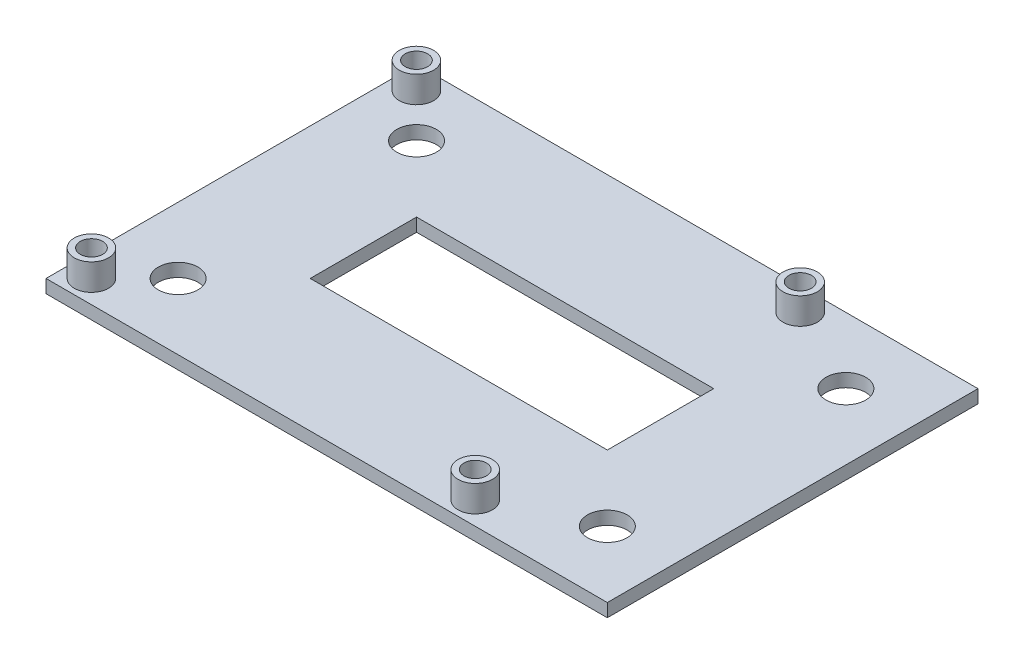
SolidWorks part; units mm, degrees
ref_plane "Front Plane" through (0, 0, 0) normal (0, 0, 1) x (1, 0, 0)
ref_plane "Top Plane" through (0, 0, 0) normal (0, 1, 0) x (1, 0, 0)
ref_plane "Right Plane" through (0, 0, 0) normal (1, 0, 0) x (0, 0, -1)
sketch "Base plate" plane through (0, 0, 0) normal (0, 1, 0) x (1, 0, 0)
  line L0 (-13.8721, -27.7771) -> (51.1097, -27.7771) construction
  line L1 (-13.8721, 23.7265) -> (71.1279, 23.7265)
  line L2 (-13.8721, 23.7265) -> (-13.8721, -32.3735)
  line L3 (71.1097, -32.3735) -> (71.1279, 23.7265)
  line L4 (47.6597, -28.9235) -> (-10.4403, -28.9235) construction
  line L7 (-13.8721, -32.3735) -> (71.1097, -32.3735) construction
  line L10 (71.1097, -32.3735) -> (-13.8721, -32.3735)
  line L24 (-10.4403, 20.2765) -> (-13.8721, 20.2765) construction
  line L25 (-10.4403, 23.7265) -> (-10.4403, 20.2765) construction
  line L26 (47.6597, 23.7265) -> (47.6597, 20.2765) construction
  line L27 (51.1097, 20.2765) -> (47.6597, 20.2765) construction
  line L28 (51.1097, -28.9235) -> (47.6597, -28.9235) construction
  line L29 (47.6597, -28.9235) -> (47.6597, -32.3735) construction
  point P12 (-13.8721, -32.3735)
  point P15 (-13.8721, 23.7265)
  point P34 (71.1279, 23.7265)
sketch "Base plate inner limits" plane through (0, 0, 0) normal (0, 1, 0) x (1, 0, 0)
  line L5 (-3.8721, 13.7265) -> (-3.8721, -22.3735) construction
  line L6 (61.1129, -22.3735) -> (-3.8721, -22.3735) construction
  line L8 (61.1129, -22.3735) -> (61.1246, 13.7265) construction
  line L9 (-3.8721, 13.7265) -> (61.1246, 13.7265) construction
sketch "Base Plate Hole" plane through (0, 0, 0) normal (0, 1, 0) x (1, 0, 0)
  line L0 (6.1279, 3.7265) -> (51.1214, 3.7265)
  line L1 (51.1162, -12.3735) -> (51.1214, 3.7265)
  line L3 (51.1162, -12.3735) -> (6.1279, -12.3735)
  line L4 (6.1279, 3.7265) -> (6.1279, -12.3735)
sketch "Wall Mount Holes" plane through (0, 0, 0) normal (0, 1, 0) x (1, 0, 0)
  circle A0 centre (-3.8721, 13.7265) radius 3
  circle A1 centre (-3.8721, -22.3735) radius 3
  circle A2 centre (61.1246, 13.7265) radius 3
  circle A3 centre (61.1129, -22.3735) radius 3
extrude "Boss-Extrude1" add sketch "Base plate" along normal blind 2
extrude "Cut-Extrude2" cut sketch "Base Plate Hole" along normal blind 2
extrude "Cut-Extrude3" cut sketch "Wall Mount Holes" along normal blind 2
sketch "Standoff Mounts" plane through (0, 2, 0) normal (0, 1, 0) x (1, 0, 0)
  circle A0 centre (-10.4403, 20.2765) radius 2.6
  circle A1 centre (47.6597, 20.2765) radius 2.6
  circle A2 centre (-10.4403, -28.9235) radius 2.6
  circle A3 centre (47.6597, -28.9235) radius 2.6
extrude "Boss-Extrude3" add sketch "Standoff Mounts" along normal blind 4
sketch "Odroid C1 Mount Holes" plane through (0, 6, 0) normal (0, 1, 0) x (1, 0, 0)
  circle A11 centre (-10.4403, -28.9235) radius 1.7
  circle A12 centre (-10.4403, 20.2765) radius 1.7
  circle A13 centre (47.6597, 20.2765) radius 1.7
  circle A14 centre (47.6597, -28.9235) radius 1.7
extrude "Cut-Extrude4" cut sketch "Odroid C1 Mount Holes" against normal blind 6
